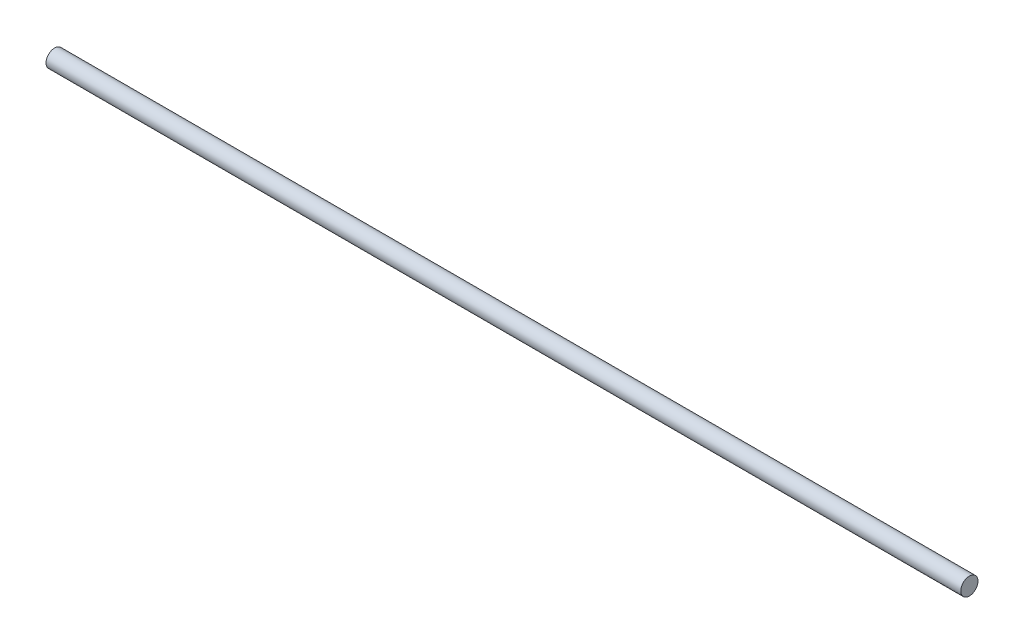
SolidWorks part; units mm, degrees
ref_plane "Plan de face" through (0, 0, 0) normal (0, 0, 1) x (1, 0, 0)
ref_plane "Plan de dessus" through (0, 0, 0) normal (0, 1, 0) x (1, 0, 0)
ref_plane "Plan de droite" through (0, 0, 0) normal (1, 0, 0) x (0, 0, -1)
sketch "Esquisse1" plane through (0, 0, 0) normal (1, 0, 0) x (0, 0, -1)
  circle A0 centre (0, 0) radius 4
  dimension "D1" = 8
extrude "Boss.-Extru.1" add sketch "Esquisse1" along normal up to surface (423.5653 mm away)
